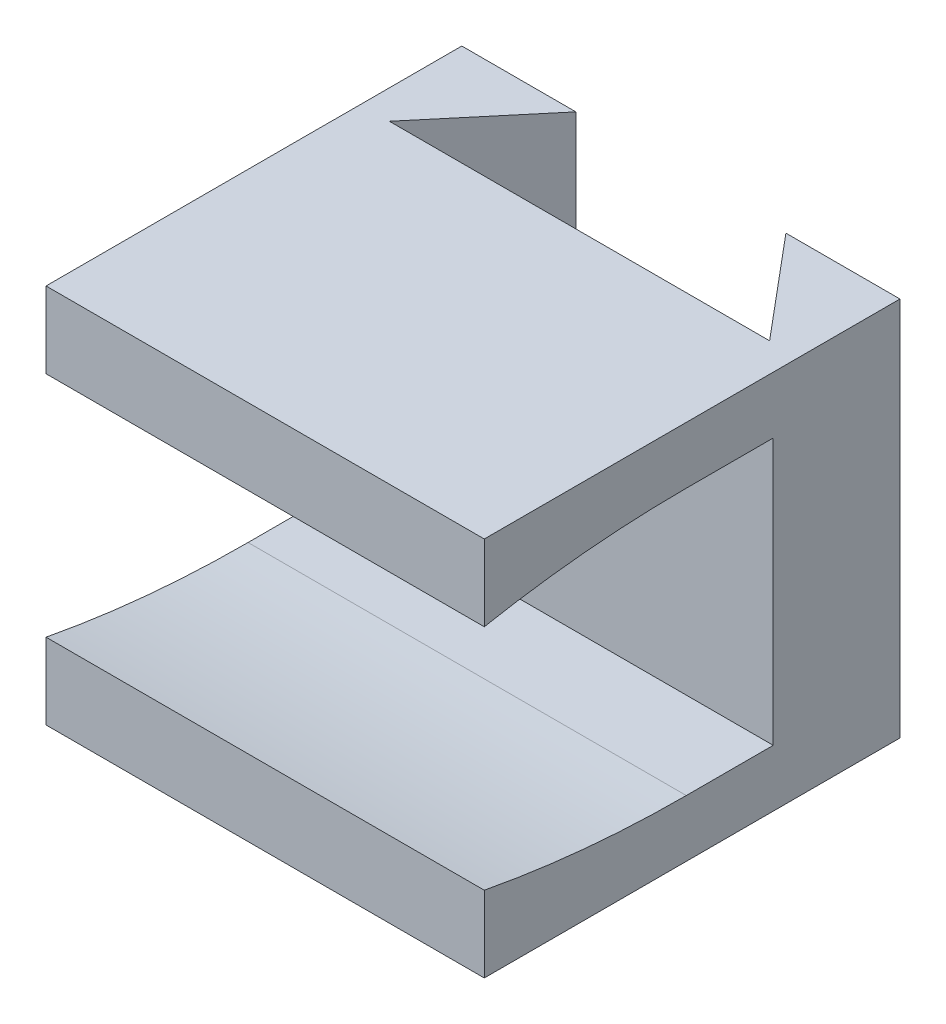
SolidWorks part; units mm, degrees
ref_plane "Front Plane" through (0, 0, 0) normal (0, 0, 1) x (1, 0, 0)
ref_plane "Top Plane" through (0, 0, 0) normal (0, 1, 0) x (1, 0, 0)
ref_plane "Right Plane" through (0, 0, 0) normal (1, 0, 0) x (0, 0, -1)
sketch "Sketch2" plane through (0, 0, 0) normal (0, 1, 0) x (1, 0, 0)
  line L0 (0, 0) -> (15, 0)
  line L1 (7.5, 0) -> (7.5, 16.3558) construction
  line L2 (15, 0) -> (11.6436, 4)
  line L3 (11.6436, 4) -> (13.1436, 4)
  line L6 (3.3564, 4) -> (1.8564, 4)
  line L7 (0, 0) -> (3.3564, 4)
  line L8 (13.1436, 4) -> (16.1436, 4)
  line L9 (16.1436, 4) -> (16.1436, -1)
  line L10 (16.1436, -1) -> (-1.1436, -1)
  line L11 (-1.1436, -1) -> (-1.1436, 4)
  line L12 (-1.1436, 4) -> (1.8564, 4)
  point P9 (0, 0)
  point P14 (0, 0)
  dimension "D1" = 15
  dimension "D2" = 1.5
  dimension "D3" = 4
  dimension "D4" = 3
  dimension "D5" = 3
  dimension "D6" = 1
  dimension "D7" = 17.2872
  dimension "D8" = 50
extrude "Boss-Extrude1" add sketch "Sketch2" along normal blind 15
sketch "Sketch4" plane through (16.1436, 0, 0) normal (1, 0, 0) x (0, 0, -1)
  line L0 (4, 7.5) -> (-4.3727, 7.5) construction
  line L1 (4, 15) -> (4, 0) construction
sketch "Sketch5" plane through (16.1436, 0, 0) normal (1, 0, 0) x (0, 0, -1)
  line L1 (-1, 15) -> (-1, 0) construction
  line L2 (-1, 2.25) -> (-4.43, 2.25)
  line L3 (-1, 0) -> (-12.4, 0)
  line L4 (-12.4, 0) -> (-12.4, 3)
  line L5 (-1, 2.25) -> (-1, 0)
  line L6 (-1, 7.5) -> (-15.1852, 7.5) construction
  line L7 (-1, 12.75) -> (-4.43, 12.75)
  line L8 (-12.4, 15) -> (-12.4, 12)
  line L9 (-1, 15) -> (-12.4, 15)
  line L10 (-1, 12.75) -> (-1, 15)
  arc A1 (-4.43, 2.25) -> (-12.4, 3) centre (-4.43, 44.9723) cw
  arc A2 (-4.43, 12.75) -> (-12.4, 12) centre (-4.43, -29.9723) ccw
  dimension "D1" = 5.25
  dimension "D2" = 3.43
  dimension "D3" = 11.4
  dimension "D4" = 2.25
  dimension "D5" = 3
extrude "Boss-Extrude2" add sketch "Sketch5" against normal blind 17.29
